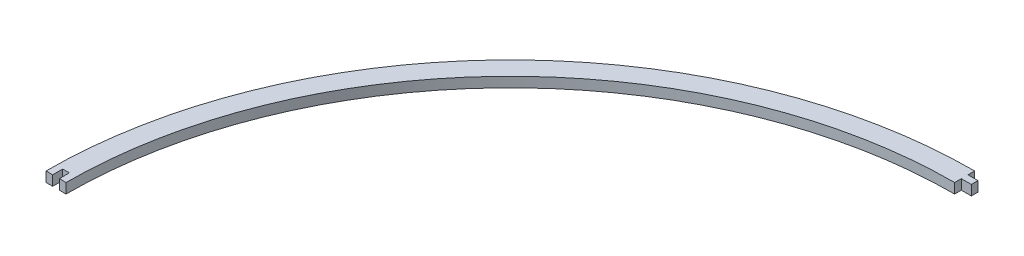
SolidWorks part; units mm, degrees
ref_plane "Front Plane" through (0, 0, 0) normal (0, 0, 1) x (1, 0, 0)
ref_plane "Top Plane" through (0, 0, 0) normal (0, 1, 0) x (1, 0, 0)
ref_plane "Right Plane" through (0, 0, 0) normal (1, 0, 0) x (0, 0, -1)
sketch "Sketch1" plane through (0, 0, 0) normal (0, 1, 0) x (1, 0, 0)
  line L0 (0, 0) -> (0, 281.686) construction
  line L1 (0, 0) -> (-294.386, 0) construction
  line L2 (0, 294.386) -> (0, 290.1527)
  line L3 (-281.686, 0) -> (-285.9193, 0)
  line L4 (0, 290.1527) -> (6.35, 290.1527)
  line L5 (6.35, 290.1527) -> (6.35, 285.9193)
  line L6 (6.35, 285.9193) -> (0, 285.9193)
  line L7 (0, 285.9193) -> (0, 281.686)
  line L8 (-285.9193, 0) -> (-285.9193, 6.35)
  line L9 (-285.9193, 6.35) -> (-290.1527, 6.35)
  line L10 (-290.1527, 6.35) -> (-290.1527, 0)
  line L11 (-290.1527, 0) -> (-294.386, 0)
  arc A0 (0, 281.686) -> (-281.686, 0) centre (0, 0) ccw
  arc A1 (0, 294.386) -> (-294.386, 0) centre (0, 0) ccw
  dimension "D1" = 12.7
  dimension "D2" = 588.772
  dimension "D3" = 6.35
  dimension "D4" = 6.35
extrude "Boss-Extrude1" add sketch "Sketch1" along normal blind 6.35
